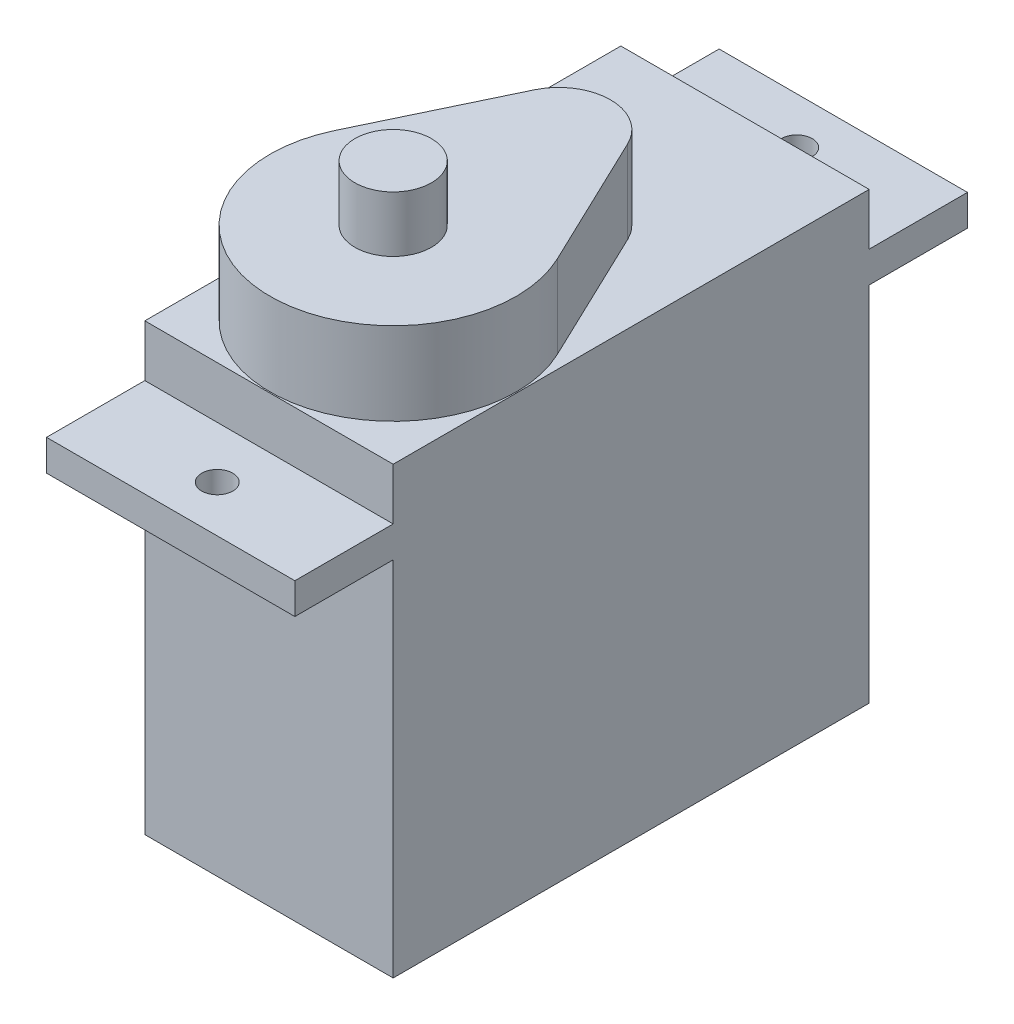
SolidWorks part; units mm, degrees
ref_plane "Front" through (0, 0, 0) normal (0, 0, 1) x (1, 0, 0)
ref_plane "Top" through (0, 0, 0) normal (0, 1, 0) x (1, 0, 0)
ref_plane "Right" through (0, 0, 0) normal (1, 0, 0) x (0, 0, -1)
sketch "Skizze1" plane through (0, 0, 0) normal (1, 0, 0) x (0, 0, -1)
  line L0 (11.5, 21.5) -> (11.5, 0) construction
  line L1 (0, 0) -> (23, 0)
  line L2 (0, 0) -> (0, 17.5)
  line L3 (0, 21.5) -> (23, 21.5)
  line L4 (23, 0) -> (23, 17.5)
  line L5 (23, 19) -> (27.75, 19)
  line L7 (23, 17.5) -> (27.75, 17.5)
  line L8 (27.75, 19) -> (27.75, 17.5)
  line L9 (0, 17.5) -> (-4.75, 17.5)
  line L10 (-4.75, 19) -> (-4.75, 17.5)
  line L11 (0, 19) -> (-4.75, 19)
  line L12 (0, 19) -> (0, 21.5)
  line L13 (23, 19) -> (23, 21.5)
  dimension "D1" = 1.5
  dimension "D2" = 32.5
  dimension "D3" = 23
  dimension "D4" = 21.5
  dimension "D5" = 2.5
extrude "Aufsatz-Linear austragen1" add sketch "Skizze1" along normal blind 12
sketch "Skizze2" plane through (0, 21.5, 0) normal (0, 1, 0) x (1, 0, 0)
  line L0 (6, 0) -> (6, 6) construction
  line L1 (12, 0) -> (0, 0) construction
  line L2 (6, 6) -> (6, 14) construction
  line L3 (3.7444, 15.0781) -> (0.6317, 8.5659)
  line L4 (8.2556, 15.0781) -> (11.3683, 8.5659)
  arc A0 (0.6317, 8.5659) -> (11.3683, 8.5659) centre (6, 6) ccw
  arc A2 (8.2556, 15.0781) -> (3.7444, 15.0781) centre (6, 14) ccw
  dimension "D1" = 11.9
  dimension "D2" = 6
  dimension "D4" = 8
extrude "Aufsatz-Linear austragen2" add sketch "Skizze2" along normal blind 4
sketch "Skizze3" plane through (0, 25.5, 0) normal (0, 1, 0) x (1, 0, 0)
  circle A0 centre (6, 6) radius 1.85
  dimension "D1" = 3.7
extrude "Aufsatz-Linear austragen3" add sketch "Skizze3" along normal blind 2.7
sketch "Skizze4" plane through (0, 19, 0) normal (0, 1, 0) x (1, 0, 0)
  line L0 (6, -4.75) -> (6, -2.5) construction
  line L1 (12, -4.75) -> (0, -4.75) construction
  line L2 (6, -2.5) -> (6, 25.5) construction
  line L3 (6, 25.5) -> (6, 27.75) construction
  line L4 (12, 27.75) -> (0, 27.75) construction
  circle A0 centre (6, -2.5) radius 0.75
  circle A1 centre (6, 25.5) radius 0.75
  point P5 (6, -2.5461)
  point P11 (6, 25.2652)
  dimension "D1" = 1.5
  dimension "D2" = 28
extrude "Schnitt-Linear austragen1" cut sketch "Skizze4" against normal through all
